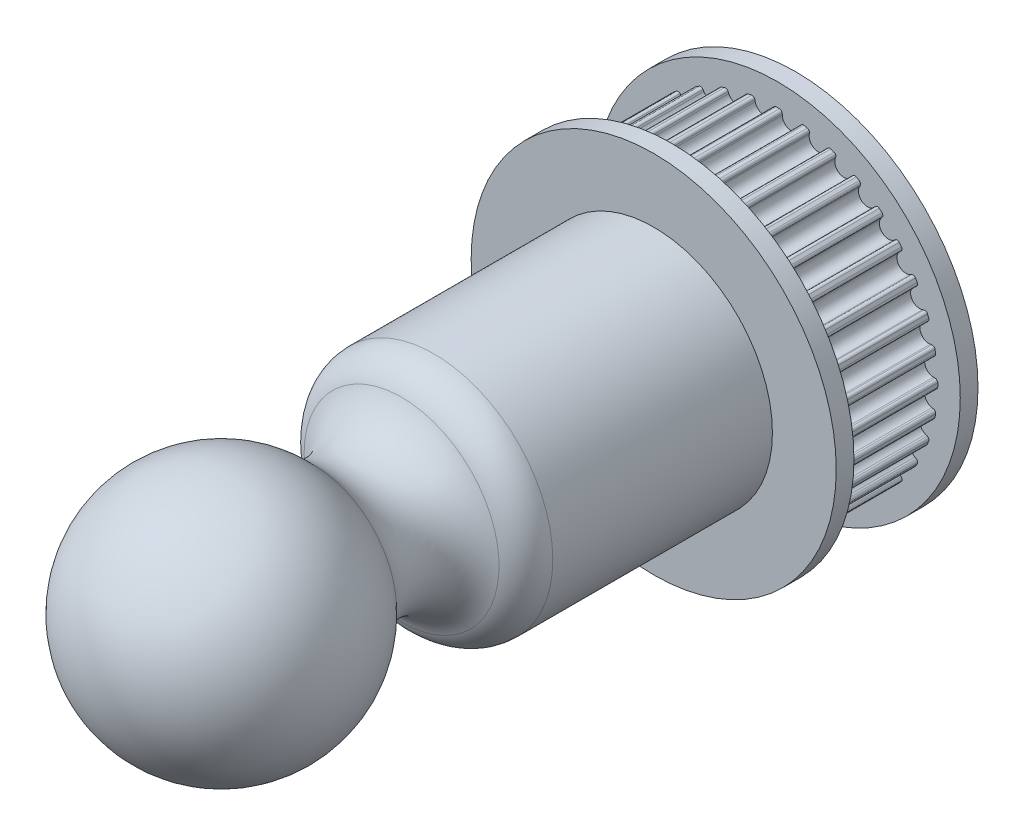
SolidWorks part; units mm, degrees
ref_plane "前视基准面" through (0, 0, 0) normal (0, 0, 1) x (1, 0, 0)
ref_plane "上视基准面" through (0, 0, 0) normal (0, 1, 0) x (1, 0, 0)
ref_plane "右视基准面" through (0, 0, 0) normal (1, 0, 0) x (0, 0, -1)
sketch "Sketch2" plane through (0, 0, 0) normal (0, 0, 1) x (1, 0, 0)
  circle A0 centre (0, 0) radius 45.15
  dimension "D1" = 90.3
extrude "Extrude1" add sketch "Sketch2" along normal blind 30
sketch "Sketch1" plane through (0, 0, 0) normal (0, 0, 1) x (1, 0, 0)
  line L0 (0, 0) -> (0, 45.835) construction
  line L1 (0, 0) -> (-3.9948, 45.6606) construction
  line L2 (-1.2656, 44.3946) -> (-1.2821, 43.9222)
  line L3 (-6.4627, 43.9399) -> (-6.3644, 43.4775)
  circle A0 centre (0, 0) radius 45.835 construction
  arc A1 (-0.4946, 45.1473) -> (-7.3526, 44.5473) centre (0, 0) ccw
  arc A2 (-6.3644, 43.4775) -> (-1.2821, 43.9222) centre (-3.8505, 44.0119) ccw
  arc A3 (-0.4946, 45.1473) -> (-1.2656, 44.3946) centre (-0.4861, 44.3673) ccw
  arc A4 (-7.3526, 44.5473) -> (-6.4627, 43.9399) centre (-7.2256, 43.7777) cw
  point P4 (45.6606, 3.9948)
  point P5 (44.2732, 11.863)
  point P6 (41.5406, 19.3707)
  point P7 (37.5458, 26.2899)
  point P8 (32.4102, 32.4102)
  point P9 (26.2899, 37.5458)
  point P10 (19.3707, 41.5406)
  point P11 (11.863, 44.2732)
  point P12 (3.9948, 45.6606)
  point P13 (-3.9948, 45.6606)
  point P14 (-11.863, 44.2732)
  point P15 (-19.3707, 41.5406)
  point P16 (-26.2899, 37.5458)
  point P17 (-32.4102, 32.4102)
  point P18 (-37.5458, 26.2899)
  point P19 (-41.5406, 19.3707)
  point P20 (-44.2732, 11.863)
  point P21 (-45.6606, 3.9948)
  point P22 (-45.6606, -3.9948)
  point P23 (-44.2732, -11.863)
  point P24 (-41.5406, -19.3707)
  point P25 (-37.5458, -26.2899)
  point P26 (-32.4102, -32.4102)
  point P27 (-26.2899, -37.5458)
  point P28 (-19.3707, -41.5406)
  point P29 (-11.863, -44.2732)
  point P30 (-3.9948, -45.6606)
  point P31 (3.9948, -45.6606)
  point P32 (11.863, -44.2732)
  point P33 (19.3707, -41.5406)
  point P34 (26.2899, -37.5458)
  point P35 (32.4102, -32.4102)
  point P36 (37.5458, -26.2899)
  point P37 (41.5406, -19.3707)
  point P38 (44.2732, -11.863)
  point P39 (45.6606, -3.9948)
  dimension "D1" = 91.67
  dimension "D2" = 90.3
  dimension "D3" = 5.14
  dimension "D4" = 3.54
  dimension "D5" = 1.56
  dimension "D6" = 7
extrude "Extrude2" cut sketch "Sketch1" along normal up to surface (30 mm away) up to face at (45.15, 0, 30)
pattern_circular "CirPattern1" count 36 over 360 about axis through (0, 0, 0) along (0, 0, 1) of "Extrude2"
sketch "Sketch3" plane through (0, 0, 30) normal (0, 0, 1) x (1, 0, 0)
  circle A0 centre (0, 0) radius 51.5
  dimension "D1" = 103
extrude "Extrude3" add sketch "Sketch3" along normal blind 5
sketch "Sketch4" plane through (0, 0, 0) normal (0, 0, -1) x (-1, 0, 0)
  circle A0 centre (0, 0) radius 51.5
  dimension "D1" = 103
extrude "Extrude4" add sketch "Sketch4" along normal blind 5
sketch "Sketch8" plane through (0, 0, 0) normal (0, 1, 0) x (1, 0, 0)
  line L0 (0, 5) -> (0, -35) construction
  line L2 (51.5, 5) -> (-51.5, 5) construction
  line L3 (-51.5, -35) -> (51.5, -35) construction
  line L4 (33.5, -35) -> (33.5, -96.9691)
  line L5 (-33.5, -35) -> (33.5, -35) construction
  line L6 (-33.5, -35) -> (-33.5, -114.8634) construction
  line L7 (0, -35) -> (33.5, -35)
  line L8 (0, -35) -> (0, -192)
  arc A0 (0, -192) -> (23.45, -131.0174) centre (0, -157) ccw
  arc A1 (27.5, -106.1342) -> (23.45, -131.0174) centre (33.5, -119.8819) ccw
  arc A2 (27.5, -106.1342) -> (33.5, -96.9691) centre (23.5, -96.9691) ccw
  point P17 (0, -157)
  dimension "D2" = 70
  dimension "D4" = 30
  dimension "D5" = 10
  dimension "D1" = 67
  dimension "D3" = 122
revolve "Revolve2" add sketch "Sketch8" angle 360 about L8
